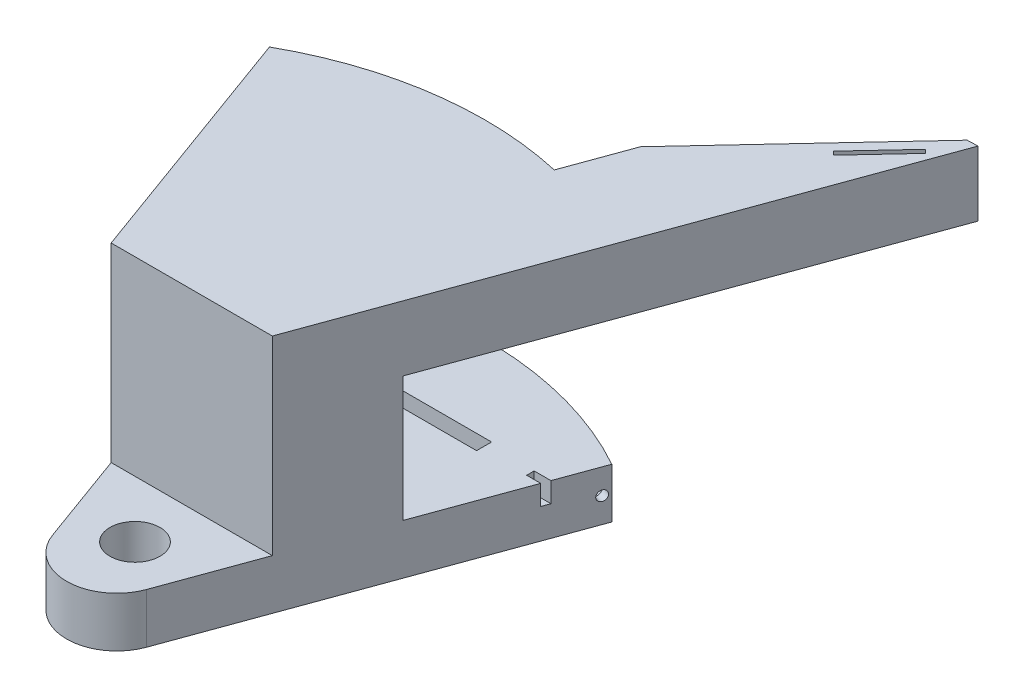
SolidWorks part; units mm, degrees
ref_plane "前视基准面" through (0, 0, 0) normal (0, 0, 1) x (1, 0, 0)
ref_plane "上视基准面" through (0, 0, 0) normal (0, 1, 0) x (1, 0, 0)
ref_plane "右视基准面" through (0, 0, 0) normal (1, 0, 0) x (0, 0, -1)
sketch "草图1" plane through (0, 0, 0) normal (0, 1, 0) x (1, 0, 0)
  line L0 (0, -1000) -> (0, 49000) construction
  line L1 (-34.202, 61.0755) -> (-9.3969, -7.0759)
  line L2 (34.202, 61.0755) -> (9.3969, -7.0759)
  circle A0 centre (0, 0) radius 70
  arc A1 (9.3969, -7.0759) -> (-9.3969, -7.0759) centre (0, -3.6557) cw
  circle A2 centre (0, 0) radius 5
  point P8 (0, -32.8937)
extrude "凸台-拉伸1" add sketch "草图1" along normal blind 48 contours A1 L0 A2 A0 L1 | L0 A1 L2 A0 A2
sketch "草图2" plane through (0, 48, 0) normal (0, 1, 0) x (1, 0, 0)
  line L0 (55.0345, 118.3122) -> (20.1256, 80.8771)
  line L1 (34.202, 61.0755) -> (9.3969, -7.0759) construction
  line L2 (36.2406, 125.1526) -> (55.0345, 118.3122)
  line L3 (36.2406, 125.1526) -> (5.4588, 40.5803)
  line L4 (5.4588, 40.5803) -> (24.2526, 33.7399)
  line L5 (55.0345, 118.3122) -> (24.2526, 33.7399)
  line L6 (36.2406, 125.1526) -> (24.2526, 33.7399) construction
  line L7 (5.4588, 40.5803) -> (55.0345, 118.3122) construction
  point P1 (30.2466, 79.4462)
  point P8 (-0.9024, -2.4793)
  dimension "D1" = 20
  dimension "D2" = 130
  dimension "D3" = 23
  dimension "D4" = 40
sketch "草图3" plane through (0, 0, 0) normal (0, 0, 1) x (1, 0, 0)
  line L0 (34.202, 48) -> (34.202, 0) construction
  line L1 (-34.202, 0) -> (-9.3969, 0) construction
  line L2 (-26.202, 8) -> (32.202, 8)
  line L3 (-26.202, 8) -> (-26.202, 2)
  line L4 (-26.202, 2) -> (32.202, 2)
  line L5 (32.202, 8) -> (32.202, 2)
  line L6 (-26.202, 8) -> (32.202, 2) construction
  line L7 (-26.202, 2) -> (32.202, 8) construction
  line L8 (-34.202, 48) -> (-34.202, 0) construction
  point P1 (3, 5)
  dimension "D1" = 2
  dimension "D2" = 8
  dimension "D3" = 6
  dimension "D4" = 2
extrude "切除-拉伸2" cut sketch "草图3" along normal blind 3 from surface starting at face at (0, 24, -65.5378)
extrude "凸台-拉伸2" add sketch "草图2" against normal blind 13
sketch "草图4" plane through (0, 0, 0) normal (1, 0, 0) x (0, 0, -1)
  line L0 (-13.6557, 48) -> (-13.6557, 0) construction
  line L1 (-13.6557, 48) -> (11.3443, 48)
  line L2 (-13.6557, 48) -> (-13.6557, 10)
  line L3 (-13.6557, 10) -> (11.3443, 10)
  line L4 (11.3443, 48) -> (11.3443, 10)
  line L5 (-13.6557, 48) -> (11.3443, 10) construction
  line L6 (-13.6557, 10) -> (11.3443, 48) construction
  line L8 (70.4669, 35) -> (30.4669, 35)
  line L9 (70.4669, 35) -> (70.4669, 10)
  line L10 (70.4669, 10) -> (30.4669, 10)
  line L11 (30.4669, 35) -> (30.4669, 10)
  line L12 (70.4669, 35) -> (30.4669, 10) construction
  line L13 (70.4669, 10) -> (30.4669, 35) construction
  line L14 (59.1533, 8) -> (67, 8) construction
  line L15 (-13.6557, 0) -> (-7.0759, 0) construction
  line L16 (118.3122, 35) -> (61.0755, 35) construction
  point P4 (-1.1557, 29)
  point P11 (50.4669, 22.5)
  dimension "D1" = 2
  dimension "D2" = 40
  dimension "D3" = 10
  dimension "D5" = 25
extrude "切除-拉伸3" cut sketch "草图4" against normal through all both and the other way through all
chamfer "倒角1" distance 5 angle 45 1 edges at (55.0345, 41.5, -118.3122)
sketch "草图6" plane through (0, 0, 0) normal (0, -1, 0) x (1, 0, 0)
  circle A0 centre (0, 0) radius 6.5
  dimension "D1" = 13
extrude "切除-拉伸4" cut sketch "草图6" against normal blind 2
sketch "草图7" plane through (0, 0, 0) normal (0, 0, 1) x (1, 0, 0)
  line L0 (-1024.202, 5) -> (48975.798, 5) construction
  line L1 (-26.202, 8) -> (-26.202, 2) construction
  line L2 (-34.202, 10) -> (-34.202, 0) construction
  circle A0 centre (-30.202, 5) radius 1.5
  point P5 (-26.202, 5)
  dimension "D1" = 3
  dimension "D2" = 4
extrude "切除-拉伸5" cut sketch "草图7" against normal blind 60
sketch "草图8" plane through (0, 10, 0) normal (0, 1, 0) x (1, 0, 0)
  line L0 (-34.202, 61.0755) -> (-16.1013, 11.3443) construction
  line L1 (-34.7582, 54.7401) -> (-25.7582, 54.7401)
  line L2 (-34.7582, 54.7401) -> (-34.7582, 45.7401)
  line L3 (-34.7582, 45.7401) -> (-25.7582, 45.7401)
  line L4 (-25.7582, 54.7401) -> (-25.7582, 45.7401)
  line L5 (-34.7582, 54.7401) -> (-25.7582, 45.7401) construction
  line L6 (-34.7582, 45.7401) -> (-25.7582, 54.7401) construction
  point P0 (-30.2582, 50.2401)
  dimension "D1" = 9
  dimension "D2" = 9
extrude "切除-拉伸6" cut sketch "草图8" against normal blind 11
sketch "草图10" plane through (10.5718, 0, 3.8478) normal (0.9397, 0, 0.342) x (0.342, 0, -0.9397)
  line L0 (-930.91, 5) -> (49069.09, 5) construction
  line L1 (69.09, 10) -> (69.09, 0) construction
  line L2 (67.59, -995) -> (67.59, 49005) construction
  circle A0 centre (67.59, 5) radius 1
  point P5 (69.09, 5)
  dimension "D1" = 2
  dimension "D2" = 1.5
extrude "切除-拉伸8" cut sketch "草图10" against normal up to surface (1.9464 mm away)
sketch "草图11" plane through (0, 0, -60) normal (0, 0, 1) x (1, 0, 0)
  circle A0 centre (-30.202, 5) radius 0.75
  dimension "D1" = 1.5
extrude "切除-拉伸9" cut sketch "草图11" against normal up to next
sketch "草图12" plane through (0, 10, 0) normal (0, 1, 0) x (1, 0, 0)
  line L1 (-1.653, 52.9115) -> (18.347, 52.9115)
  line L2 (-1.653, 52.9115) -> (-1.653, 49.9115)
  line L3 (-1.653, 49.9115) -> (18.347, 49.9115)
  line L4 (18.347, 52.9115) -> (18.347, 49.9115)
  line L5 (-1.653, 52.9115) -> (18.347, 49.9115) construction
  line L6 (-1.653, 49.9115) -> (18.347, 52.9115) construction
  point P0 (8.347, 51.4115)
  dimension "D1" = 3
  dimension "D2" = 20
  dimension "D3" = 15
extrude "切除-拉伸10" cut sketch "草图12" against normal blind 11
sketch "草图13" plane through (0, 10, 0) normal (0, 1, 0) x (1, 0, 0)
  line L0 (-976.6169, 51.4115) -> (49023.3831, 51.4115) construction
  line L1 (18.347, 49.9115) -> (18.347, 52.9115) construction
  line L3 (27.6086, 52.1615) -> (31.4769, 52.1615)
  line L4 (27.6086, 52.1615) -> (27.6086, 50.6615)
  line L5 (27.6086, 50.6615) -> (31.4769, 50.6615)
  line L6 (31.4769, 52.1615) -> (31.4769, 50.6615)
  line L7 (27.6086, 52.1615) -> (31.4769, 50.6615) construction
  line L8 (27.6086, 50.6615) -> (31.4769, 52.1615) construction
  point P4 (18.347, 51.4115)
  point P5 (29.5428, 51.4115)
  dimension "D1" = 1.5
extrude "切除-拉伸11" cut sketch "草图13" against normal blind 4
sketch "草图14" plane through (0, 48, 0) normal (0, 1, 0) x (1, 0, 0)
  line L0 (51.6245, 114.6554) -> (20.1256, 80.8771) construction
  line L1 (49.7661, 108.2233) -> (49.0348, 108.9053)
  line L2 (49.7661, 108.2233) -> (40.9002, 98.7157)
  line L3 (40.9002, 98.7157) -> (40.1688, 99.3977)
  line L4 (49.0348, 108.9053) -> (40.1688, 99.3977)
  line L5 (49.7661, 108.2233) -> (40.1688, 99.3977) construction
  line L6 (40.9002, 98.7157) -> (49.0348, 108.9053) construction
  line L9 (53.7303, 114.729) -> (16.1013, 11.3443) construction
  point P4 (44.9675, 103.8105)
  dimension "D1" = 1
  dimension "D2" = 13
  dimension "D3" = 13
  dimension "D4" = 1
  dimension "D5" = 90
  dimension "D6" = 4.5
  dimension "D7" = 14
extrude "切除-拉伸12" cut sketch "草图14" against normal up to next
